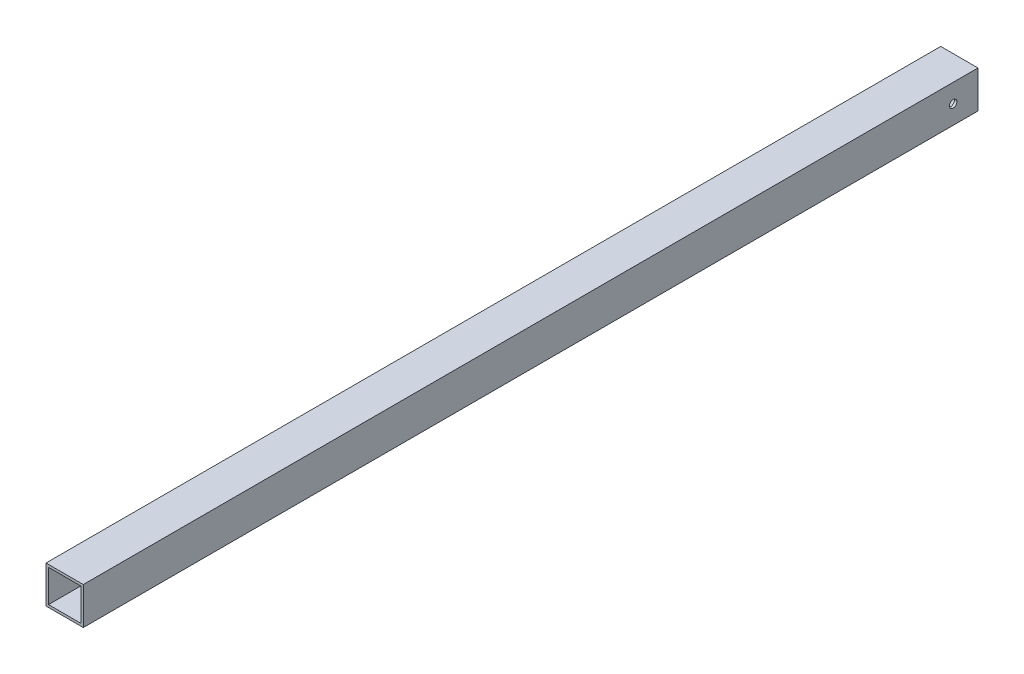
SolidWorks part; units mm, degrees
material "Thornel Mat VMA"
ref_plane "前视基准面" through (0, 0, 0) normal (0, 0, 1) x (1, 0, 0)
ref_plane "上视基准面" through (0, 0, 0) normal (0, 1, 0) x (1, 0, 0)
ref_plane "右视基准面" through (0, 0, 0) normal (1, 0, 0) x (0, 0, -1)
sketch "草图1" plane through (0, 0, 0) normal (0, 0, 1) x (1, 0, 0)
  line L1 (-7.5, 7.5) -> (7.5, 7.5)
  line L2 (-7.5, 7.5) -> (-7.5, -7.5)
  line L3 (-7.5, -7.5) -> (7.5, -7.5)
  line L4 (7.5, 7.5) -> (7.5, -7.5)
  line L5 (-7.5, 7.5) -> (7.5, -7.5) construction
  line L6 (-7.5, -7.5) -> (7.5, 7.5) construction
  line L7 (-6.5, 6.5) -> (6.5, 6.5)
  line L8 (-6.5, 6.5) -> (-6.5, -6.5)
  line L9 (-6.5, -6.5) -> (6.5, -6.5)
  line L10 (6.5, 6.5) -> (6.5, -6.5)
  line L11 (-6.5, 6.5) -> (6.5, -6.5) construction
  line L12 (-6.5, -6.5) -> (6.5, 6.5) construction
  point P0 (0, 0)
  point P5 (0, 0)
  dimension "D1" = 15
  dimension "D2" = 13
extrude "凸台-拉伸1" add sketch "草图1" along normal blind 360
sketch "草图2" plane through (-7.5, 0, 0) normal (-1, 0, 0) x (0, 0, 1)
  line L0 (0, 7.5) -> (0, -7.5) construction
  circle A0 centre (10, 0) radius 1.5
  dimension "D1" = 3
  dimension "D2" = 10
extrude "切除-拉伸1" cut sketch "草图2" against normal blind 25
